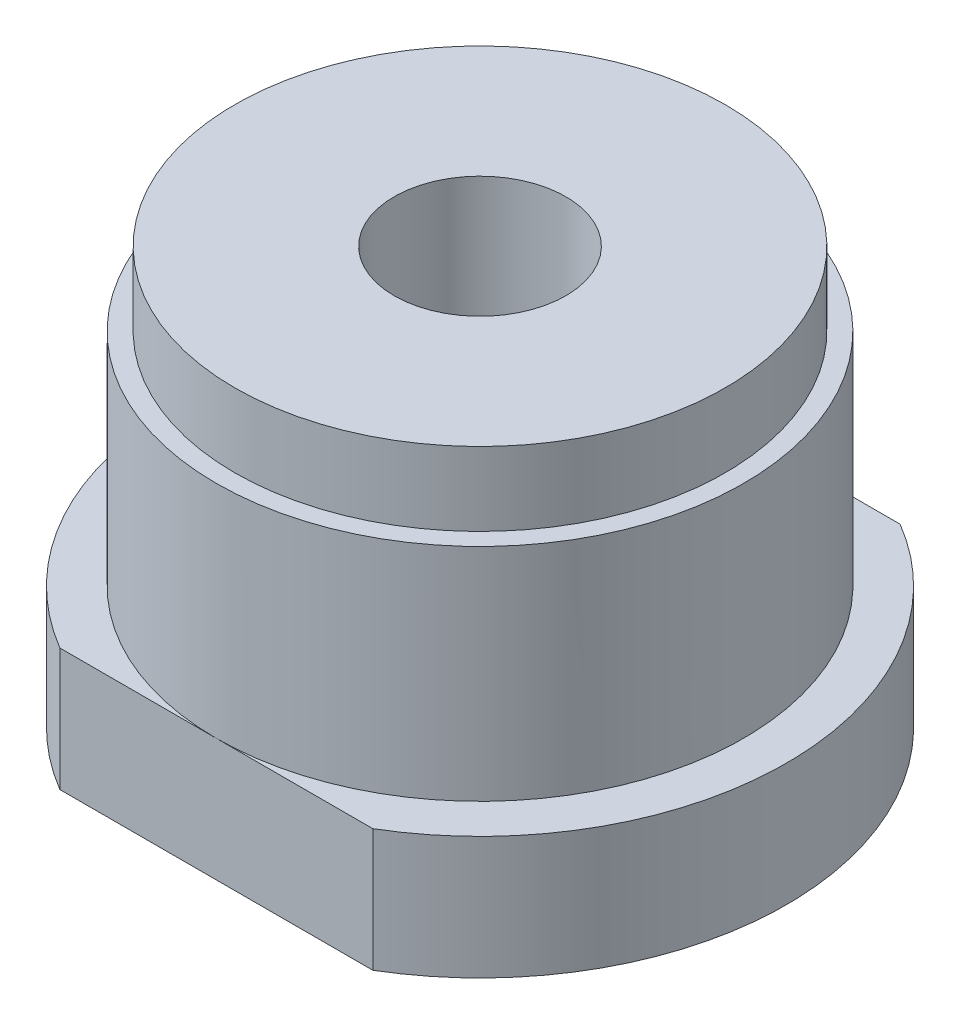
SolidWorks part; units mm, degrees
ref_plane "Front Plane" through (0, 0, 0) normal (0, 0, 1) x (1, 0, 0)
ref_plane "Top Plane" through (0, 0, 0) normal (0, 1, 0) x (1, 0, 0)
ref_plane "Right Plane" through (0, 0, 0) normal (1, 0, 0) x (0, 0, -1)
sketch "Sketch1" plane through (0, 0, 0) normal (0, 1, 0) x (1, 0, 0)
  circle A0 centre (0, 0) radius 12.5
  dimension "D1" = 25
extrude "Boss-Extrude1" add sketch "Sketch1" along normal blind 17
sketch "Sketch2" plane through (0, 17, 0) normal (0, 1, 0) x (1, 0, 0)
  circle A0 centre (0, 0) radius 3.5
  dimension "D1" = 7
extrude "Cut-Extrude1" cut sketch "Sketch2" against normal offset from surface (15 mm away) 2 up to face at (0, 0, 12.5)
sketch "Sketch3" plane through (0, 0, 0) normal (1, 0, 0) x (0, 0, -1)
  line L0 (0, 9.35) -> (0, -9.35) construction
  line L1 (11.825, 0) -> (-11.825, 0) construction
  circle A0 centre (8, 3) radius 1.5
  dimension "D1" = 3
  dimension "D2" = 8
  dimension "D3" = 3
extrude "Cut-Extrude2" [suppressed] cut sketch "Sketch3" against normal through all and the other way through all
mirror "Mirror1" [suppressed] about plane through (0, 0, 0) normal (0, 0, 1)
sketch "Sketch4" plane through (0, 17, 0) normal (0, 1, 0) x (1, 0, 0)
  circle A0 centre (0, 0) radius 10
  dimension "D1" = 20
extrude "Cut-Extrude3" cut sketch "Sketch4" against normal offset from surface (12 mm away) 5 flip side to cut up to face at (0, 0, 12.5)
sketch "Sketch5" plane through (0, 0, 0) normal (0, -1, 0) x (1, 0, 0)
  line L0 (9.35, 0) -> (-9.35, 0) construction
  circle A0 centre (-8, 0) radius 1.25
  dimension "D1" = 2.5
  dimension "D2" = 8
extrude "Cut-Extrude4" cut sketch "Sketch5" against normal blind 10
mirror "Mirror2" about plane through (0, 0, 0) normal (1, 0, 0) of "Cut-Extrude4"
sketch "Sketch6" plane through (0, 5, 0) normal (0, 1, 0) x (1, 0, 0)
  line L0 (0, -9.35) -> (0, 9.35) construction
  circle A0 centre (0, 12.5) radius 2.5
  circle A1 centre (0, 0) radius 10 construction
  dimension "D1" = 5
extrude "Cut-Extrude5" [suppressed] cut sketch "Sketch6" against normal blind 5
sketch "Sketch8" plane through (0, 5, 0) normal (0, 1, 0) x (1, 0, 0)
  circle A0 centre (0, 0) radius 10.75
  circle A1 centre (0, 0) radius 4
  dimension "D1" = 21.5
extrude "Boss-Extrude3" add sketch "Sketch8" along normal blind 9
sketch "Sketch7" plane through (0, 5, 0) normal (0, 1, 0) x (1, 0, 0)
  line L1 (-11.0868, 15.6344) -> (11.839, 15.6344)
  line L2 (-11.0868, 15.6344) -> (-11.0868, 10.75)
  line L3 (-11.0868, 10.75) -> (11.839, 10.75)
  line L4 (11.839, 15.6344) -> (11.839, 10.75)
  circle A0 centre (0, 0) radius 10.75 construction
extrude "Cut-Extrude6" cut sketch "Sketch7" against normal through all
mirror "Mirror3" about plane through (0, 0, 0) normal (0, 0, 1) of "Cut-Extrude6"
pattern_circular "CirPattern1" [suppressed] count 12 over 360
fillet "Fillet1" [suppressed] radius 1
